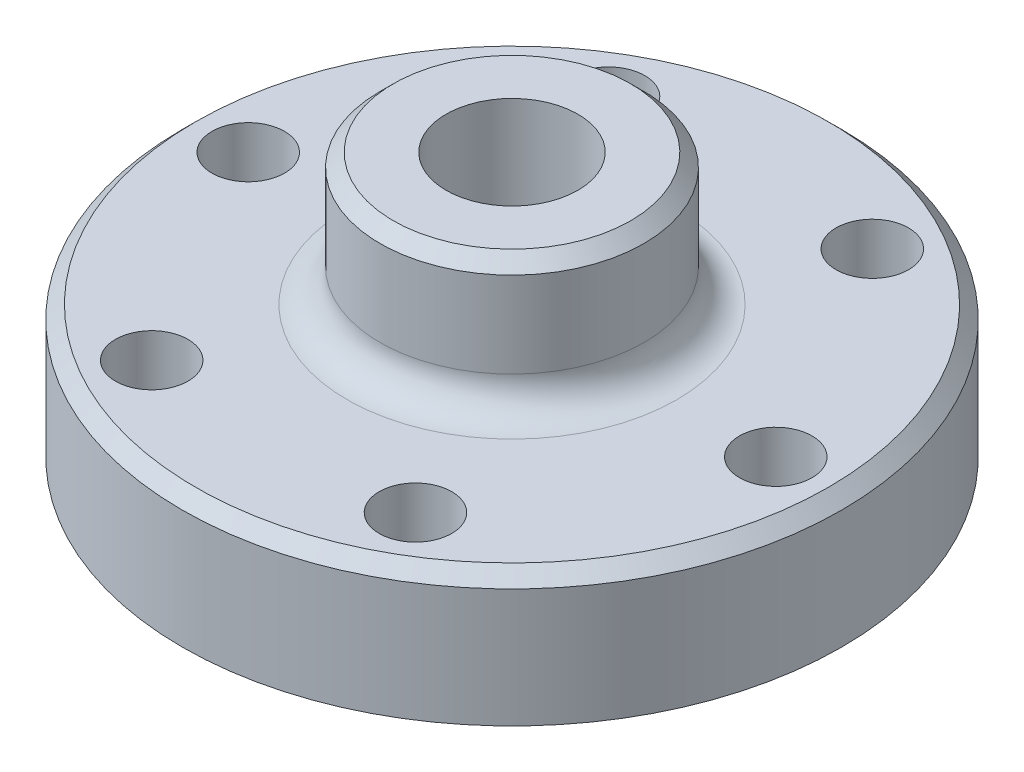
SolidWorks part; units mm, degrees
ref_plane "前视基准面" through (0, 0, 0) normal (0, 0, 1) x (1, 0, 0)
ref_plane "上视基准面" through (0, 0, 0) normal (0, 1, 0) x (1, 0, 0)
ref_plane "右视基准面" through (0, 0, 0) normal (1, 0, 0) x (0, 0, -1)
other "Configuration Table"
sketch "草图1" plane through (0, 0, 0) normal (0, 0, 1) x (1, 0, 0)
  line L0 (0, -641.5808) -> (0, 31437.4579) construction
  line L1 (-641.5808, 0) -> (31437.4579, 0) construction
  line L2 (30, 2.5) -> (50, 2.5)
  line L3 (10, 0) -> (30, 0)
  line L4 (10, 0) -> (10, 42.5)
  line L5 (10, 42.5) -> (18, 42.5)
  line L6 (20, 27.5) -> (20, 40.5)
  line L7 (50, 2.5) -> (50, 20.5)
  line L8 (48, 22.5) -> (25, 22.5)
  line L9 (30, 0) -> (30, 2.5)
  line L10 (-30, 0) -> (-30, 2.5)
  line L11 (-48, 22.5) -> (-25, 22.5)
  line L12 (-50, 2.5) -> (-50, 20.5)
  line L13 (-20, 27.5) -> (-20, 40.5)
  line L14 (-10, 42.5) -> (-18, 42.5)
  line L15 (-10, 0) -> (-10, 42.5)
  line L16 (-10, 0) -> (-30, 0)
  line L17 (-30, 2.5) -> (-50, 2.5)
  line L18 (-20, 40.5) -> (-18, 42.5)
  line L19 (18, 42.5) -> (20, 40.5)
  line L20 (-50, 20.5) -> (-48, 22.5)
  line L21 (50, 20.5) -> (48, 22.5)
  arc A0 (-25, 22.5) -> (-20, 27.5) centre (-25, 27.5) ccw
  arc A1 (25, 22.5) -> (20, 27.5) centre (25, 27.5) cw
  point P6 (20, 42.5)
  point P12 (50, 22.5)
  point P15 (-50, 22.5)
  point P18 (-20, 42.5)
  point P31 (-20, 22.5)
  point P34 (20, 22.5)
  dimension "D8" = 5
  dimension "D1" = 20
  dimension "D2" = 40
  dimension "D3" = 20
  dimension "D4" = 42.5
  dimension "D5" = 40
  dimension "D6" = 60
  dimension "D7" = 100
revolve "旋转1" add sketch "草图1" angle 360 about L0
sketch "草图2" plane through (0, 22.5, 0) normal (0, 1, 0) x (1, 0, 0)
  line L0 (-1000, 0) -> (49000, 0) construction
  line L1 (0, -1000) -> (0, 49000) construction
  circle A0 centre (-40, 0) radius 5.5
  circle A1 centre (-20, 34.641) radius 5.5
  circle A2 centre (20, 34.641) radius 5.5
  circle A3 centre (40, 0) radius 5.5
  circle A4 centre (20, -34.641) radius 5.5
  circle A5 centre (-20, -34.641) radius 5.5
  point P7 (0, 0)
  point P20 (0, 0)
  dimension "D1" = 11
  dimension "D2" = 40
  dimension "D3" = 6
extrude "切除-拉伸1" cut sketch "草图2" against normal through all
